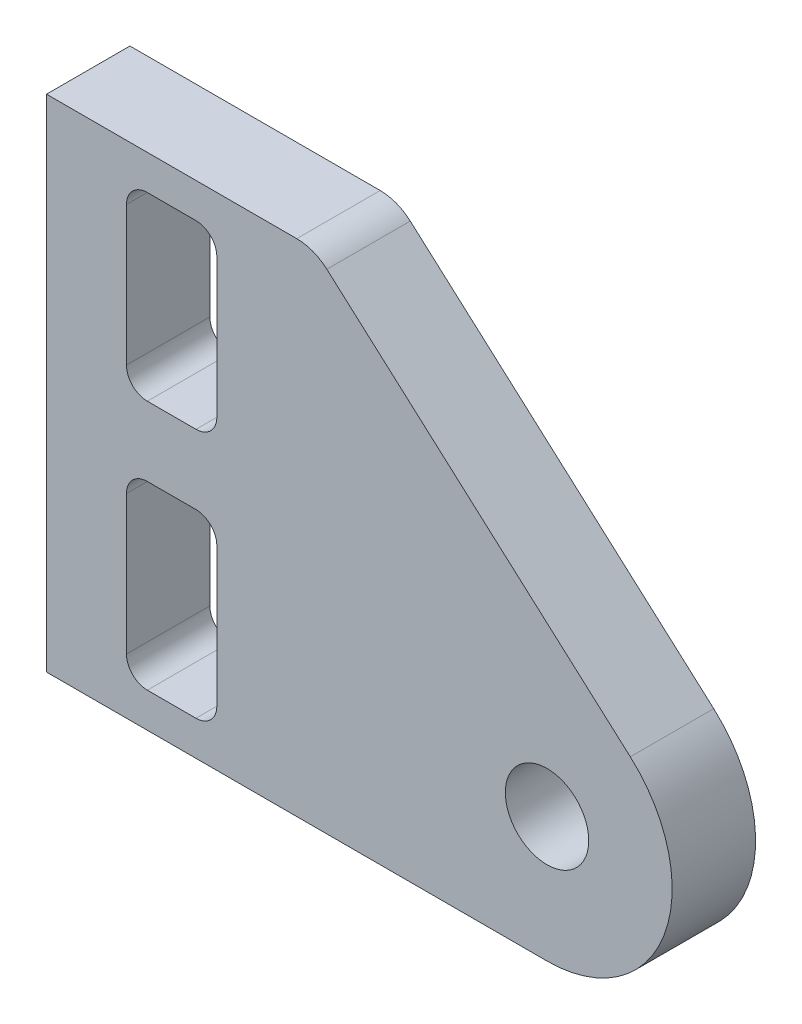
SolidWorks part; units mm, degrees
ref_plane "Alzado" through (0, 0, 0) normal (0, 0, 1) x (1, 0, 0)
ref_plane "Planta" through (0, 0, 0) normal (0, 1, 0) x (1, 0, 0)
ref_plane "Vista lateral" through (0, 0, 0) normal (1, 0, 0) x (0, 0, -1)
sketch "Model" plane through (0, 0, 0) normal (0, 0, 1) x (1, 0, 0)
  line L0 (201.0979, 264.6465) -> (183.0979, 264.6465)
  line L1 (186.7229, 265.8965) -> (188.4729, 265.8965)
  line L2 (189.2229, 266.6465) -> (189.2229, 271.6465)
  line L3 (188.4729, 272.3965) -> (186.7229, 272.3965)
  line L4 (185.9729, 271.6465) -> (185.9729, 266.6465)
  line L5 (192.0979, 282.6465) -> (183.0979, 282.6465)
  line L6 (193.1792, 282.2345) -> (204.0924, 272.5055)
  line L7 (186.7229, 274.896) -> (188.4729, 274.896)
  line L8 (189.2229, 275.646) -> (189.2229, 280.646)
  line L9 (188.4729, 281.396) -> (186.7229, 281.396)
  line L10 (185.9729, 280.646) -> (185.9729, 275.646)
  line L11 (183.0979, 282.6465) -> (183.0979, 264.6465)
  arc A0 (201.0979, 264.6465) -> (204.0924, 272.5055) centre (201.0979, 269.1465) ccw
  circle A1 centre (201.0979, 269.1465) radius 1.5
  arc A2 (185.9729, 266.6465) -> (186.7229, 265.8965) centre (186.7229, 266.6465) ccw
  arc A3 (188.4729, 265.8965) -> (189.2229, 266.6465) centre (188.4729, 266.6465) ccw
  arc A4 (189.2229, 271.6465) -> (188.4729, 272.3965) centre (188.4729, 271.6465) ccw
  arc A5 (186.7229, 272.3965) -> (185.9729, 271.6465) centre (186.7229, 271.6465) ccw
  arc A6 (193.1792, 282.2345) -> (192.0979, 282.6465) centre (192.0979, 281.0215) ccw
  arc A7 (185.9729, 275.646) -> (186.7229, 274.896) centre (186.7229, 275.646) ccw
  arc A8 (188.4729, 274.896) -> (189.2229, 275.646) centre (188.4729, 275.646) ccw
  arc A9 (189.2229, 280.646) -> (188.4729, 281.396) centre (188.4729, 280.646) ccw
  arc A10 (186.7229, 281.396) -> (185.9729, 280.646) centre (186.7229, 280.646) ccw
extrude "Saliente-Extruir1" add sketch "Model" along normal blind 3
